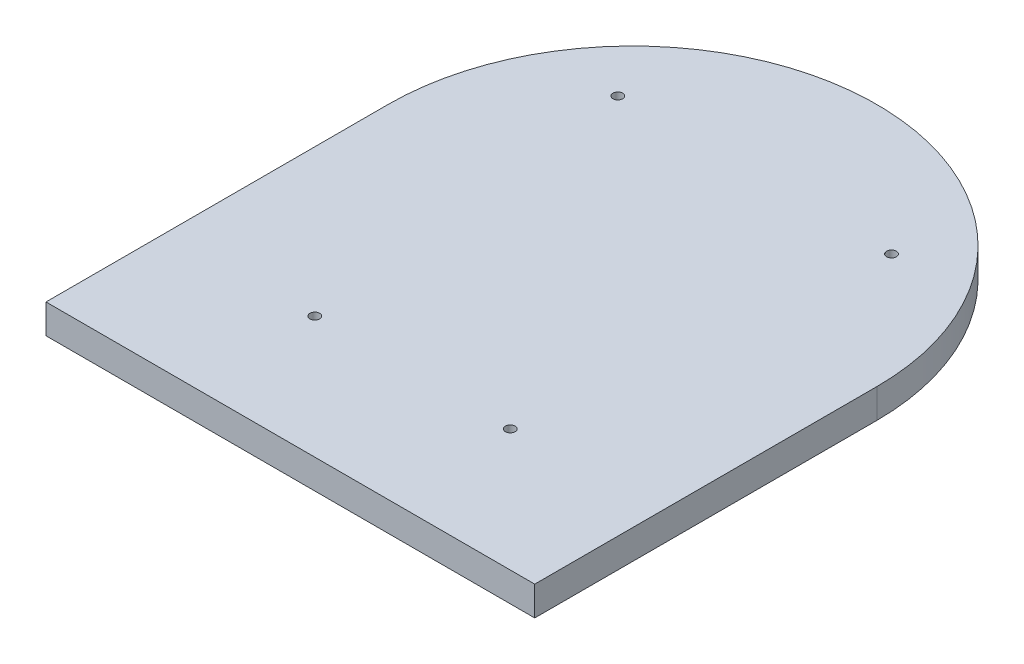
SolidWorks part; units mm, degrees
ref_plane "Front Plane" through (0, 0, 0) normal (0, 0, 1) x (1, 0, 0)
ref_plane "Top Plane" through (0, 0, 0) normal (0, 1, 0) x (1, 0, 0)
ref_plane "Right Plane" through (0, 0, 0) normal (1, 0, 0) x (0, 0, -1)
sketch "Sketch1" plane through (0, 0, 0) normal (0, 1, 0) x (1, 0, 0)
  line L0 (50, 0) -> (50, -34.8498) construction
  line L1 (0, 0) -> (100, 0)
  line L2 (0, 0) -> (0, 70)
  line L4 (100, 0) -> (100, 70)
  arc A0 (0, 70) -> (100, 70) centre (50, 70) cw
  circle A1 centre (22, 95) radius 1
  circle A2 centre (78, 95) radius 1
  circle A3 centre (30, 25) radius 1
  circle A4 centre (70, 25) radius 1
  point P7 (50, 120)
  dimension "D3" = 2
  dimension "D4" = 56
  dimension "D1" = 100
  dimension "D2" = 120
  dimension "D5" = 28
  dimension "D6" = 40
  dimension "D7" = 20
  dimension "D8" = 70
  dimension "D9" = 25
extrude "Boss-Extrude1" add sketch "Sketch1" along normal blind 6
